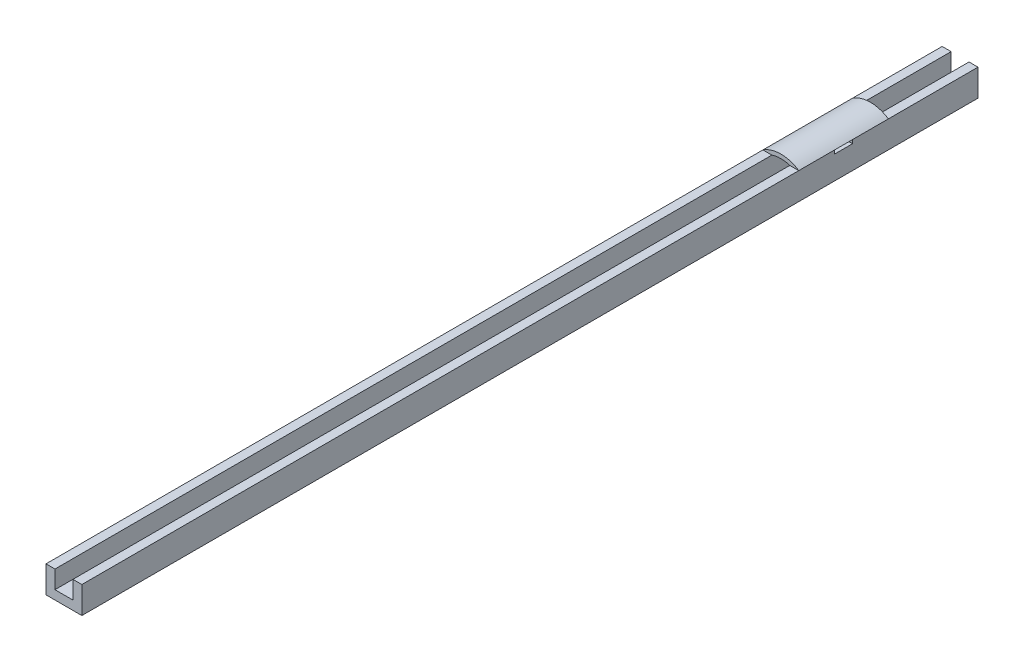
SolidWorks part; units mm, degrees
ref_plane "Спереди" through (0, 0, 0) normal (0, 0, 1) x (1, 0, 0)
ref_plane "Сверху" through (0, 0, 0) normal (0, 1, 0) x (1, 0, 0)
ref_plane "Справа" through (0, 0, 0) normal (1, 0, 0) x (0, 0, -1)
sketch "Эскиз2" plane through (0, 0, 0) normal (0, 0, 1) x (1, 0, 0)
  line L0 (-413.04, 0) -> (412.6764, 0) construction
  line L1 (0, 292.8763) -> (0, -291.5385) construction
  line L2 (0, 0) -> (-10, 0)
  line L3 (10, 0) -> (0, 0)
  line L4 (-10, 0) -> (-10, 20)
  line L5 (10, 0) -> (10, 20)
  line L6 (-10, 20) -> (-20, 20)
  line L7 (-20, 20) -> (-20, -10)
  line L8 (-20, -10) -> (0, -10)
  line L9 (10, 20) -> (20, 20)
  line L10 (20, 20) -> (20, -10)
  line L11 (20, -10) -> (0, -10)
  point P4 (0, -9.9118)
  dimension "D1" = 30
  dimension "D2" = 10
sketch3d "Трехмерный эскиз1"
  line L0 (-20, 20, 0) -> (-20, -10, 0) construction
  line L2 (20, 20, 0) -> (20, -10, 0) construction
  line L3 (0, 0, 0) -> (0, 0, 17.5928) construction
extrude "Бобышка-Вытянуть1" add sketch "Эскиз2" along normal blind 1000
sketch "Эскиз3" plane through (0, 0, 0) normal (0, 0, 1) x (1, 0, 0)
sketch3d "Трехмерный эскиз2"
  line L0 (0, 0, 100) -> (0, 50, 100) construction
  line L5 (0, 0, 0) -> (0, 0, 1099.0655) construction
  point P2 (0, 0, 0)
sketch3d "Трехмерный эскиз3"
  line L0 (0, 10, 100) -> (-43.0487, 10, 100) construction
  line L1 (0, 10, 100) -> (34.3664, 10, 100) construction
sketch3d "Трехмерный эскиз4"
  line L0 (0, 0, 100) -> (0, 50, 100) construction
  line L1 (0, 10, 100) -> (-43.0487, 10, 100) construction
  line L2 (0, 10, 100) -> (34.3664, 10, 100) construction
sketch "Эскиз5" plane through (0, 0, 100) normal (0, 0, 1) x (1, 0, 0)
  line L0 (-20, -10) -> (20, -10) construction
  line L1 (20, -10) -> (20, 20) construction
  line L2 (10, 20) -> (10, 0) construction
  line L3 (-20, 20) -> (-10, 20)
  line L4 (10, 20) -> (20, 20)
  arc A0 (-20, 20) -> (20, 20) centre (0, -10) cw
  arc A1 (-10, 20) -> (10, 20) centre (0, -10) cw
extrude "Бобышка-Вытянуть2" add sketch "Эскиз5" along normal blind 100
sketch3d "Трехмерный эскиз5"
  line L0 (30, 16, 160) -> (30, 20, 160)
  line L1 (30, 35.4974, 200) -> (30, -16, 200) construction
  line L2 (30, 16, 160) -> (30, 16, 140)
  line L4 (30, 16, 140) -> (30, 20, 140)
  line L5 (30, 20, 160) -> (30, 20, 140)
extrude "Вырез-Вытянуть3" cut sketch "Трехмерный эскиз5" along direction (1, 0, 0) on the side of the normal up to surface (20 mm away) and the other way through all
